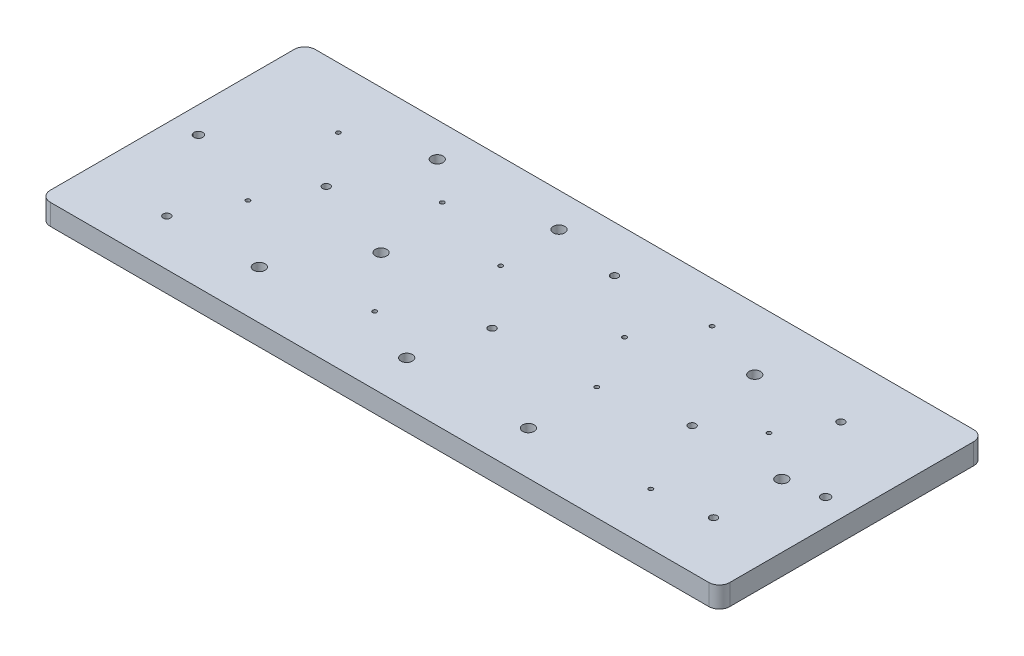
SolidWorks part; units mm, degrees
material "1060 Alloy"
ref_plane "Front Plane" through (0, 0, 0) normal (0, 0, 1) x (1, 0, 0)
ref_plane "Top Plane" through (0, 0, 0) normal (0, 1, 0) x (1, 0, 0)
ref_plane "Right Plane" through (0, 0, 0) normal (1, 0, 0) x (0, 0, -1)
sketch "Sketch1" plane through (0, 0, 0) normal (0, 1, 0) x (1, 0, 0)
  line L1 (0, 0) -> (650, 0)
  line L2 (0, 0) -> (0, 253.35)
  line L3 (0, 253.35) -> (650, 253.35)
  line L4 (650, 0) -> (650, 253.35)
  dimension "D1" = 253.35
  dimension "D2" = 650
extrude "Boss-Extrude1" add sketch "Sketch1" along normal blind 20 contours L2 L3 L4 L1
fillet "Fillet1" radius 10 4 edges at (0, 10, 0) (650, 10, 0) (650, 10, -253.35) (0, 10, -253.35)
sketch "Sketch4" plane through (0, 20, 0) normal (0, 1, 0) x (1, 0, 0)
  point P0 (90.0583, 195.4825)
  point P2 (255.539, 64.7324)
  point P4 (396.504, 162.795)
  point P6 (544.9599, 152.5801)
  point P8 (534.745, 49.7506)
  point P10 (278.0117, 162.795)
  point P12 (102.9971, 96.0579)
  point P14 (429.1915, 213.8692)
  point P16 (424.4246, 108.3157)
  point P18 (197.6548, 187.3106)
hole_wizard "Ø4.0 (4) Diameter Hole1" positions "Sketch4" profile "Sketch3" hole size "Ø4.0" standard "DIN" end condition through all
sketch "Sketch3" plane through (90.0583, 20, -195.4825) normal (1, 0, 0) x (0, 0, 1)
  line L0 (0, 0) -> (0, 20)
  line L1 (0, 20) -> (2, 20)
  line L2 (2, 20) -> (2, 0)
  line L5 (2, 0) -> (0, 0)
  line L11 (0, -6.35) -> (0, 107.95) construction
  dimension "Thru Hole Dia." = 4
  dimension "Thru Hole Depth" = 20
sketch "Sketch7" plane through (0, 20, 0) normal (0, 1, 0) x (1, 0, 0)
  point P0 (128.8748, 145.0892)
  point P4 (77.1195, 44.3026)
  point P6 (325.681, 106.9538)
  point P8 (340.6628, 209.1023)
  point P10 (502.0575, 121.9355)
  point P12 (570.1565, 196.1635)
  point P14 (588.5433, 55.8795)
  point P16 (0, 0)
  point P17 (0, 0)
hole_wizard "Ø7.0 (7) Diameter Hole1" positions "Sketch7" profile "Sketch6" hole size "Ø7.0" standard "DIN" end condition through all
sketch "Sketch6" plane through (128.8748, 20, -145.0892) normal (1, 0, 0) x (0, 0, 1)
  line L0 (0, 0) -> (0, 20)
  line L1 (0, 20) -> (3.5, 20)
  line L2 (3.5, 20) -> (3.5, 0)
  line L5 (3.5, 0) -> (0, 0)
  line L11 (0, -6.35) -> (0, 107.95) construction
  dimension "Thru Hole Dia." = 7
  dimension "Thru Hole Depth" = 20
sketch "Sketch10" plane through (0, 20, 0) normal (0, 1, 0) x (1, 0, 0)
  point P0 (209.9126, 116.4876)
  point P2 (425.7866, 41.5787)
  point P4 (489.7997, 194.1205)
  point P6 (309.3372, 41.5787)
  point P8 (163.6053, 46.3456)
  point P10 (159.5193, 220.6791)
  point P12 (275.9687, 220.6791)
  point P14 (589.2243, 120.5736)
hole_wizard "Ø11.0 (11) Diameter Hole1" positions "Sketch10" profile "Sketch9" hole size "Ø11.0" standard "DIN" end condition through all
sketch "Sketch9" plane through (209.9126, 20, -116.4876) normal (1, 0, 0) x (0, 0, 1)
  line L0 (0, 0) -> (0, 20)
  line L1 (0, 20) -> (5.5, 20)
  line L2 (5.5, 20) -> (5.5, 0)
  line L5 (5.5, 0) -> (0, 0)
  line L11 (0, -6.35) -> (0, 107.95) construction
  dimension "Thru Hole Dia." = 11
  dimension "Thru Hole Depth" = 20
sketch "Sketch11" plane through (0, 20, 0) normal (0, 1, 0) x (1, 0, 0)
  line L0 (50, 253.35) -> (50, 0) construction
  line L1 (10, 253.35) -> (640, 253.35) construction
  line L2 (10, 0) -> (640, 0) construction
  line L3 (50, 126.675) -> (0, 126.675) construction
  line L4 (0, 10) -> (0, 243.35) construction
  line L5 (600, 253.35) -> (600, 0) construction
  line L6 (600, 126.675) -> (650, 126.675) construction
  line L7 (650, 10) -> (650, 243.35) construction
  point P17 (625, 126.675)
  point P19 (25, 126.675)
  dimension "D1" = 50
  dimension "D2" = 50
hole_wizard "M8 Clearance Hole1" positions "Sketch11" profile "Sketch12" hole size "M8" standard "DIN"
sketch "Sketch12" plane through (25, 20, -126.675) normal (1, 0, 0) x (0, 0, 1)
  line L0 (0, 0) -> (0, 32.5236)
  line L1 (0, 32.5236) -> (4.2, 30)
  line L2 (4.2, 30) -> (4.2, 0)
  line L5 (4.2, 0) -> (0, 0)
  line L10 (0, 32.5236) -> (-4.2, 30) construction
  line L11 (0, -6.35) -> (0, 107.95) construction
  dimension "Hole Dia." = 8.4
  dimension "Hole Depth" = 30
  dimension "Drill Angle" = 118
sketch "Sketch13" plane through (0, 0, 0) normal (0, -1, 0) x (-1, 0, 0)
  line L0 (-30, 0) -> (-30, 253.35) construction
  line L1 (-10, 0) -> (-640, 0) construction
  line L2 (-10, 253.35) -> (-640, 253.35) construction
  line L3 (-620, 0) -> (-620, 253.35) construction
  line L4 (-30, 60) -> (0, 60) construction
  line L5 (0, 10) -> (0, 243.35) construction
  line L6 (-30, 193.35) -> (0, 193.35) construction
  line L7 (-620, 60) -> (-650, 60) construction
  line L8 (-650, 10) -> (-650, 243.35) construction
  line L9 (-620, 193.35) -> (-650, 193.35) construction
  circle A0 centre (-15, 60) radius 2
  circle A1 centre (-15, 193.35) radius 2
  circle A2 centre (-635, 60) radius 2
  circle A3 centre (-635, 193.35) radius 2
  dimension "D1" = 30
  dimension "D2" = 30
  dimension "D3" = 60
  dimension "D4" = 60
  dimension "D5" = 60
extrude "Cut-Extrude1" [suppressed] cut sketch "Sketch13" against normal through all
